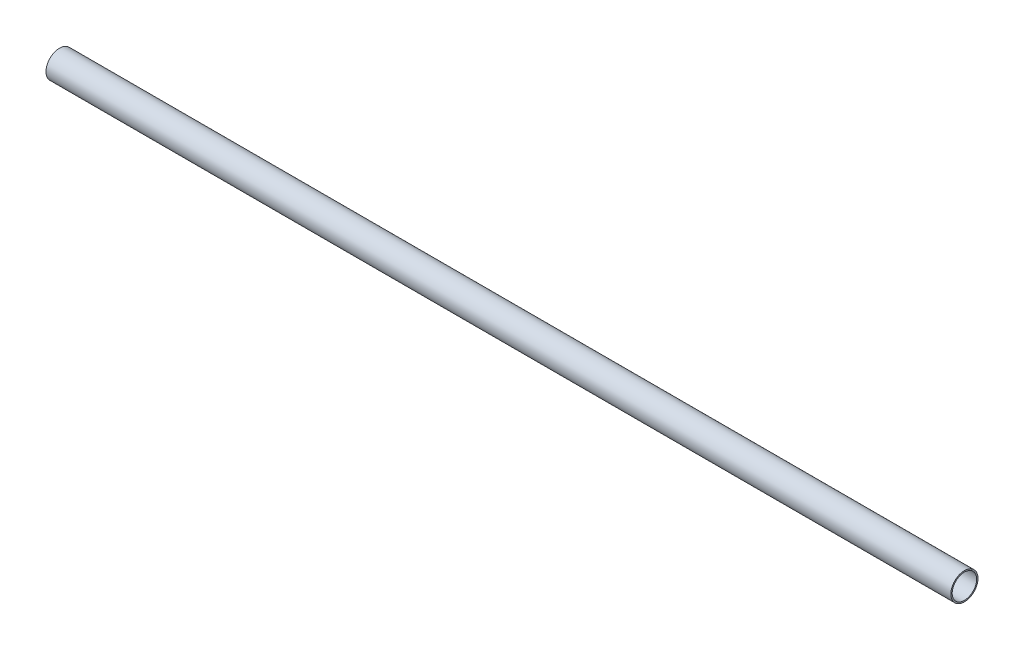
SolidWorks part; units mm, degrees
ref_plane "Front Plane" through (0, 0, 0) normal (0, 0, 1) x (1, 0, 0)
ref_plane "Top Plane" through (0, 0, 0) normal (0, 1, 0) x (1, 0, 0)
ref_plane "Right Plane" through (0, 0, 0) normal (1, 0, 0) x (0, 0, -1)
sketch "Sketch1" plane through (0, 0, 0) normal (1, 0, 0) x (0, 0, -1)
  circle A0 centre (0, 0) radius 15
  circle A1 centre (0, 0) radius 13.5
  dimension "D1" = 30
  dimension "D2" = 27
extrude "Boss-Extrude1" add sketch "Sketch1" along normal blind 1000
